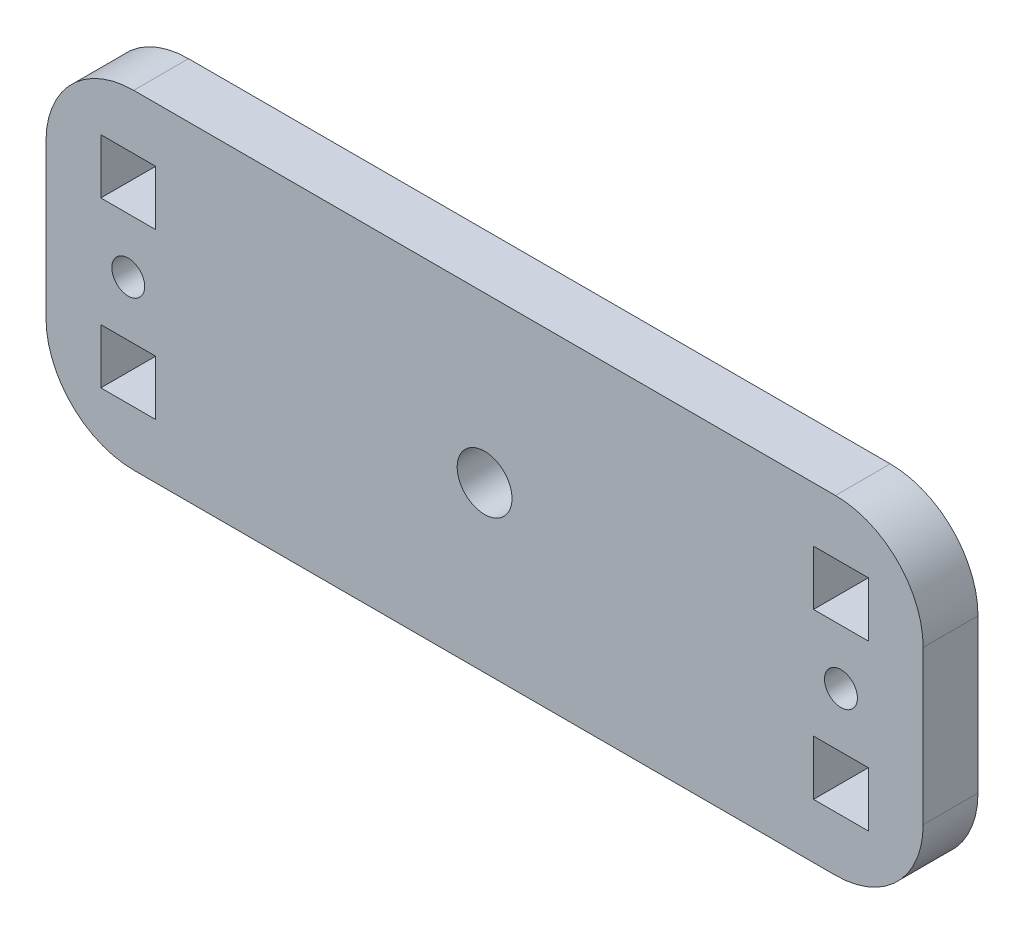
SolidWorks part; units mm, degrees
ref_plane "Plan de face" through (0, 0, 0) normal (0, 0, 1) x (1, 0, 0)
ref_plane "Plan de dessus" through (0, 0, 0) normal (0, 1, 0) x (1, 0, 0)
ref_plane "Plan de droite" through (0, 0, 0) normal (1, 0, 0) x (0, 0, -1)
sketch "Esquisse1" plane through (0, 0, 0) normal (0, 0, 1) x (1, 0, 0)
  line L0 (0, 15) -> (80, 15) construction
  line L1 (8, 0) -> (72, 0)
  line L2 (0, 8) -> (0, 22)
  line L3 (8, 30) -> (72, 30)
  line L4 (80, 8) -> (80, 22)
  line L5 (5, 25) -> (10, 25)
  line L6 (5, 25) -> (5, 20)
  line L7 (5, 20) -> (10, 20)
  line L8 (10, 25) -> (10, 20)
  line L17 (70, 25) -> (75, 25)
  line L18 (70, 25) -> (70, 20)
  line L19 (70, 20) -> (75, 20)
  line L20 (75, 25) -> (75, 20)
  line L21 (75, 5) -> (75, 10)
  line L22 (70, 10) -> (75, 10)
  line L23 (70, 5) -> (70, 10)
  line L24 (70, 5) -> (75, 5)
  line L33 (10, 5) -> (10, 10)
  line L34 (5, 10) -> (10, 10)
  line L35 (5, 5) -> (5, 10)
  line L36 (5, 5) -> (10, 5)
  line L37 (72.5, 20) -> (72.5, 10) construction
  line L38 (7.5, 20) -> (7.5, 10) construction
  arc A0 (8, 0) -> (0, 8) centre (8, 8) cw
  arc A1 (72, 0) -> (80, 8) centre (72, 8) ccw
  arc A2 (72, 30) -> (80, 22) centre (72, 22) cw
  arc A3 (0, 22) -> (8, 30) centre (8, 22) cw
  circle A4 centre (7.5, 15) radius 1.5
  circle A5 centre (72.5, 15) radius 1.5
  circle A8 centre (40, 15) radius 2.5
  point P7 (0, 0)
  point P12 (80, 30)
  point P15 (0, 30)
  dimension "D3" = 8
  dimension "D10" = 10
  dimension "D13" = 3
  dimension "D9" = 3
  dimension "D8" = 5
  dimension "D2" = 60
  dimension "D4" = 5
  dimension "D5" = 5
  dimension "D6" = 5
  dimension "D7" = 5
  dimension "D11" = 5
extrude "Boss.-Extru.1" add sketch "Esquisse1" along normal blind 5
